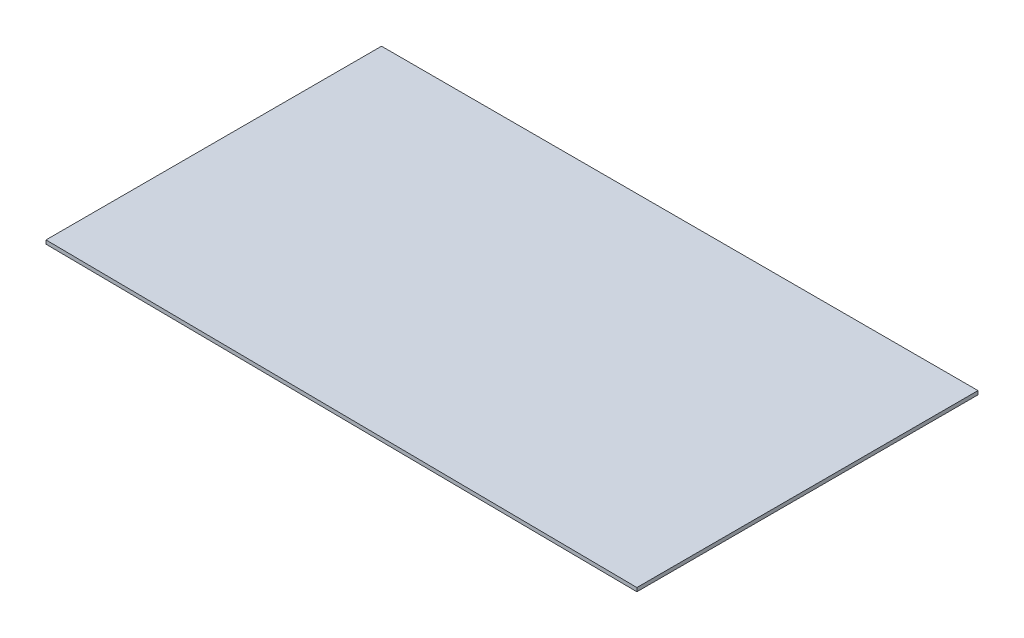
SolidWorks part; units mm, degrees
ref_plane "Front Plane" through (0, 0, 0) normal (0, 0, 1) x (1, 0, 0)
ref_plane "Top Plane" through (0, 0, 0) normal (0, 1, 0) x (1, 0, 0)
ref_plane "Right Plane" through (0, 0, 0) normal (1, 0, 0) x (0, 0, -1)
sketch "Sketch2" plane through (0, 0, 0) normal (0, 1, 0) x (1, 0, 0)
  line L0 (-70, 35) -> (70, 35) construction
  line L1 (70, 35) -> (70, -35) construction
  line L2 (70, -35) -> (-70, -35) construction
  line L3 (-70, -35) -> (-70, 35) construction
  line L4 (-80, 45) -> (80, 45) construction
  line L5 (80, 45) -> (80, -45) construction
  line L8 (80, -45) -> (-80, -45) construction
  line L9 (-80, -45) -> (-80, 45) construction
  line L10 (-80, 45) -> (80, -45) construction
  line L11 (-80, -45) -> (80, 45) construction
sketch "Sketch3" plane through (0, 0, 0) normal (0, 1, 0) x (1, 0, 0)
  line L0 (-80, 45) -> (80, 45)
  line L1 (80, 45) -> (80, -46.5056)
  line L2 (80, -46.5056) -> (-80, -45)
  line L3 (-80, -45) -> (-80, 45)
extrude "Boss-Extrude1" add sketch "Sketch3" along normal blind 1
sketch "Sketch4" plane through (0, 0, 0) normal (0, -1, 0) x (1, 0, 0)
  line L1 (70, 35) -> (-70, 35) construction
  line L4 (-70.35, 37.9795) -> (-70.35, 32.0205) construction
  line L5 (-70.35, 35) -> (-73, 35) construction
  line L6 (-69.65, 37.9795) -> (-69.65, 32.0205) construction
  line L7 (-70, 35) -> (-70, -35) construction
  line L8 (-70, 35) -> (-70, -35) construction
  line L9 (-70.35, 35) -> (-73.35, 35) construction
  line L10 (-69.65, 35) -> (-66.65, 35) construction
  circle A2 centre (-70, 35) radius 3 construction
  point P11 (70, 35)
  point P12 (70, -35)
  point P13 (-70, -35)
  point P15 (-70.35, 35)
  point P16 (-70.35, 35)
  point P17 (-70, 27.2435)
  point P20 (-69.65, 35)
  point P22 (-67, 35)
  line B0 (-70.35, 35) -> (-69.65, 35) construction
  line B1 (-70.35, 37.9795) -> (-70.35, 32.0205)
  line B2 (-69.65, 37.9795) -> (-69.65, 32.0205)
  ellipse B3 centre (-69.65, 35) end of major axis (-66.65, 35) minor radius 2.9795 (-69.65, 37.9795) -> (-69.65, 32.0205) cw
  ellipse B4 centre (-70.35, 35) end of major axis (-73.35, 35) minor radius 2.9795 (-70.35, 37.9795) -> (-70.35, 32.0205) ccw
  line B5 (69.65, 35) -> (70.35, 35) construction
  line B6 (69.65, 37.9795) -> (69.65, 32.0205)
  line B7 (70.35, 37.9795) -> (70.35, 32.0205)
  ellipse B8 centre (70.35, 35) end of major axis (73.35, 35) minor radius 2.9795 (70.35, 37.9795) -> (70.35, 32.0205) cw
  ellipse B9 centre (69.65, 35) end of major axis (66.65, 35) minor radius 2.9795 (69.65, 37.9795) -> (69.65, 32.0205) ccw
  line B10 (69.65, -35) -> (70.35, -35) construction
  line B11 (69.65, -32.0205) -> (69.65, -37.9795)
  line B12 (70.35, -32.0205) -> (70.35, -37.9795)
  ellipse B13 centre (70.35, -35) end of major axis (73.35, -35) minor radius 2.9795 (70.35, -32.0205) -> (70.35, -37.9795) cw
  ellipse B14 centre (69.65, -35) end of major axis (66.65, -35) minor radius 2.9795 (69.65, -32.0205) -> (69.65, -37.9795) ccw
  line B15 (-70.35, -32.0205) -> (-70.35, -37.9795)
  line B16 (-69.65, -32.0205) -> (-69.65, -37.9795)
  ellipse B17 centre (-69.65, -35) end of major axis (-66.65, -35) minor radius 2.9795 (-69.65, -32.0205) -> (-69.65, -37.9795) cw
  ellipse B18 centre (-70.35, -35) end of major axis (-73.35, -35) minor radius 2.9795 (-70.35, -32.0205) -> (-70.35, -37.9795) ccw
  dimension "D2" = 3
  dimension "D3" = 3
sketch_block_instance "Block2-1"
sketch_block "Block2" parameters "D1"=0.7
sketch_block_instance "Block2-2"
sketch_block_instance "Block2-3"
sketch_block_instance "Block2-4"
extrude "Boss-Extrude2" add sketch "Sketch4" along normal blind 2.7
sketch "Sketch5" plane through (0, 0, 0) normal (0, -1, 0) x (1, 0, 0)
  circle A0 centre (-70, 35) radius 3
  circle A1 centre (70, 35) radius 3
  circle A2 centre (70, -35) radius 3
  circle A3 centre (-70, -35) radius 3
extrude "Cut-Extrude1" cut sketch "Sketch5" along normal blind 2 flip side to cut
